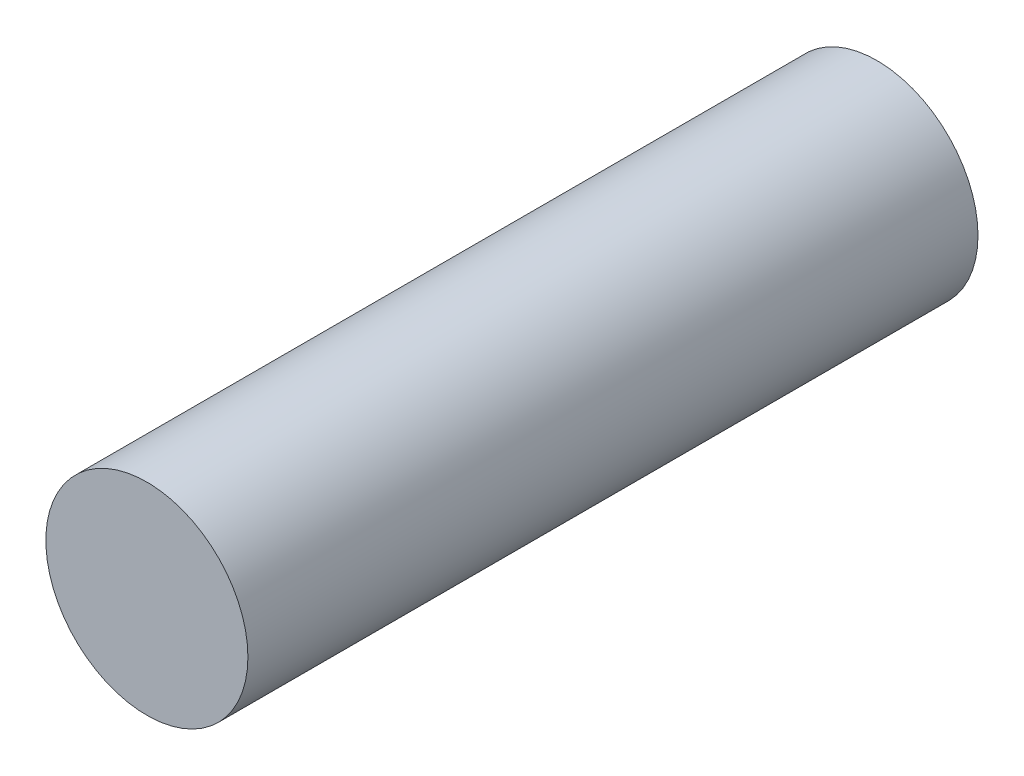
SolidWorks part; units mm, degrees
ref_plane "前视基准面" through (0, 0, 0) normal (0, 0, 1) x (1, 0, 0)
ref_plane "上视基准面" through (0, 0, 0) normal (0, 1, 0) x (1, 0, 0)
ref_plane "右视基准面" through (0, 0, 0) normal (1, 0, 0) x (0, 0, -1)
other "Configuration Table"
sketch "草图1" plane through (0, 0, 0) normal (0, 0, 1) x (1, 0, 0)
  circle A0 centre (0, 0) radius 3.8
  dimension "diameter" = 7.6
extrude "Cable" add sketch "草图1" along normal blind 27.4591
